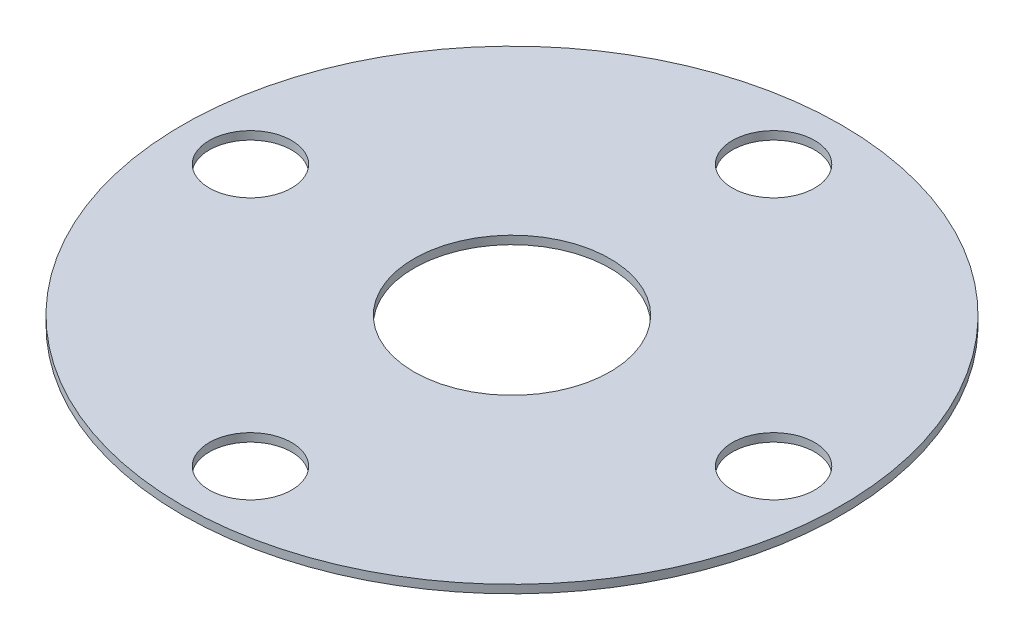
SolidWorks part; units mm, degrees
ref_plane "Front Plane" through (0, 0, 0) normal (0, 0, 1) x (1, 0, 0)
ref_plane "Top Plane" through (0, 0, 0) normal (0, 1, 0) x (1, 0, 0)
ref_plane "Right Plane" through (0, 0, 0) normal (1, 0, 0) x (0, 0, -1)
sketch "Sketch1" plane through (0, 0, 0) normal (0, 1, 0) x (1, 0, 0)
  circle A0 centre (0, 0) radius 9.525
  circle A1 centre (0, 0) radius 25.4 construction
  circle A2 centre (0, 25.4) radius 4
  circle A3 centre (25.4, 0) radius 4
  circle A4 centre (0, -25.4) radius 4
  circle A5 centre (-25.4, 0) radius 4
  circle A6 centre (0, 0) radius 32.004
  point P15 (0, 0)
  dimension "D1" = 19.05
  dimension "D2" = 50.8
  dimension "D3" = 8
  dimension "D5" = 64.008
  dimension "D4" = 4
extrude "Boss-Extrude1" add sketch "Sketch1" along normal blind 0.8
